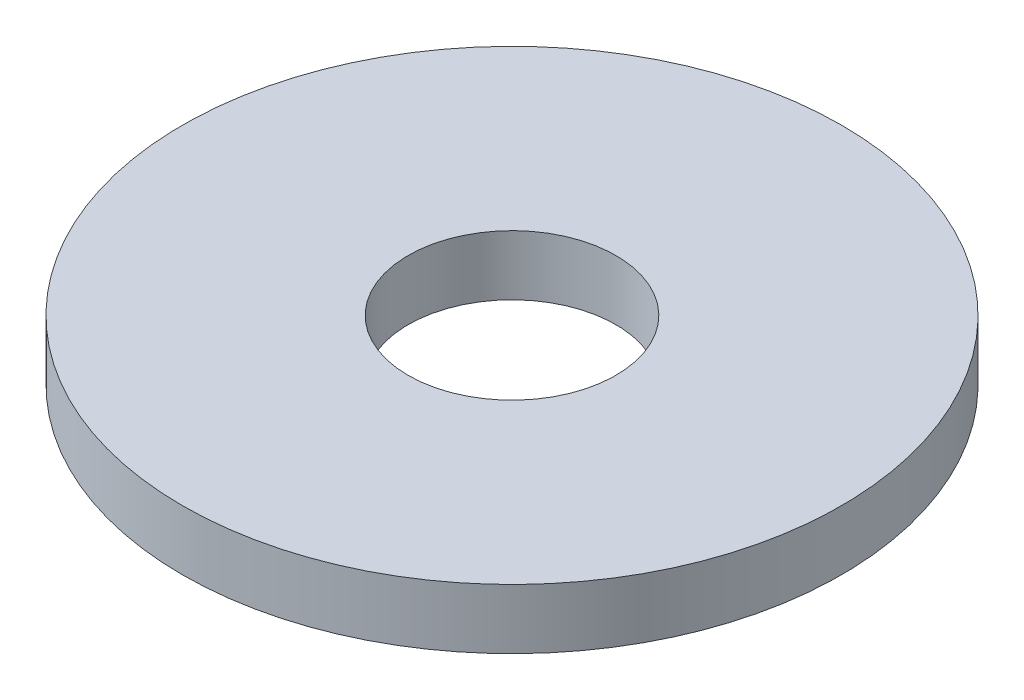
SolidWorks part; units mm, degrees
ref_plane "Front Plane" through (0, 0, 0) normal (0, 0, 1) x (1, 0, 0)
ref_plane "Top Plane" through (0, 0, 0) normal (0, 1, 0) x (1, 0, 0)
ref_plane "Right Plane" through (0, 0, 0) normal (1, 0, 0) x (0, 0, -1)
sketch "Sketch1" plane through (0, 0, 0) normal (0, 1, 0) x (1, 0, 0)
  circle A0 centre (0, 0) radius 2.6
  circle A1 centre (0, 0) radius 8.25
  dimension "D1" = 5.2
  dimension "D2" = 16.5
extrude "body" add sketch "Sketch1" along normal blind 1.5 contours A0 | A1
